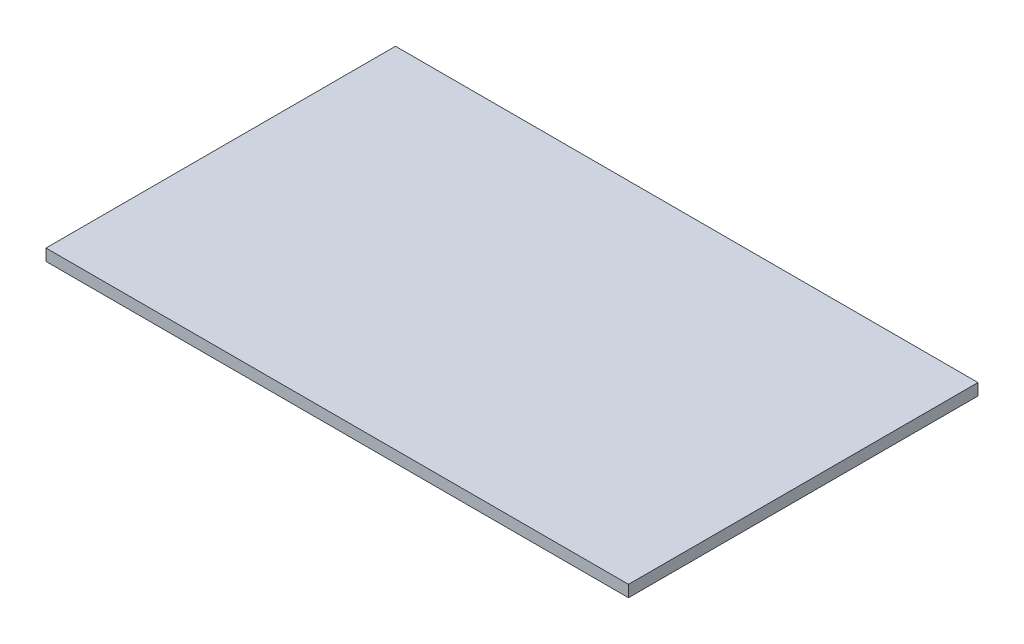
SolidWorks part; units mm, degrees
material "PW80:Mi:0:10:Ar:0:-1:Sc:1:Re:29:Ts:30:31:32:33:34:35:"
ref_plane "Plan1" through (0, 0, 0) normal (0, 0, 1) x (1, 0, 0)
ref_plane "Plan2" through (0, 0, 0) normal (0, 1, 0) x (1, 0, 0)
ref_plane "Plan3" through (0, 0, 0) normal (1, 0, 0) x (0, 0, -1)
sketch "Esquisse1" plane through (0, 0, 0) normal (0, 1, 0) x (1, 0, 0)
  line L1 (0, 0) -> (5000, 0)
  line L2 (0, 0) -> (0, 3000)
  line L3 (0, 3000) -> (5000, 3000)
  line L4 (5000, 0) -> (5000, 3000)
extrude "Base-Extrusion" add sketch "Esquisse1" along normal blind 100
